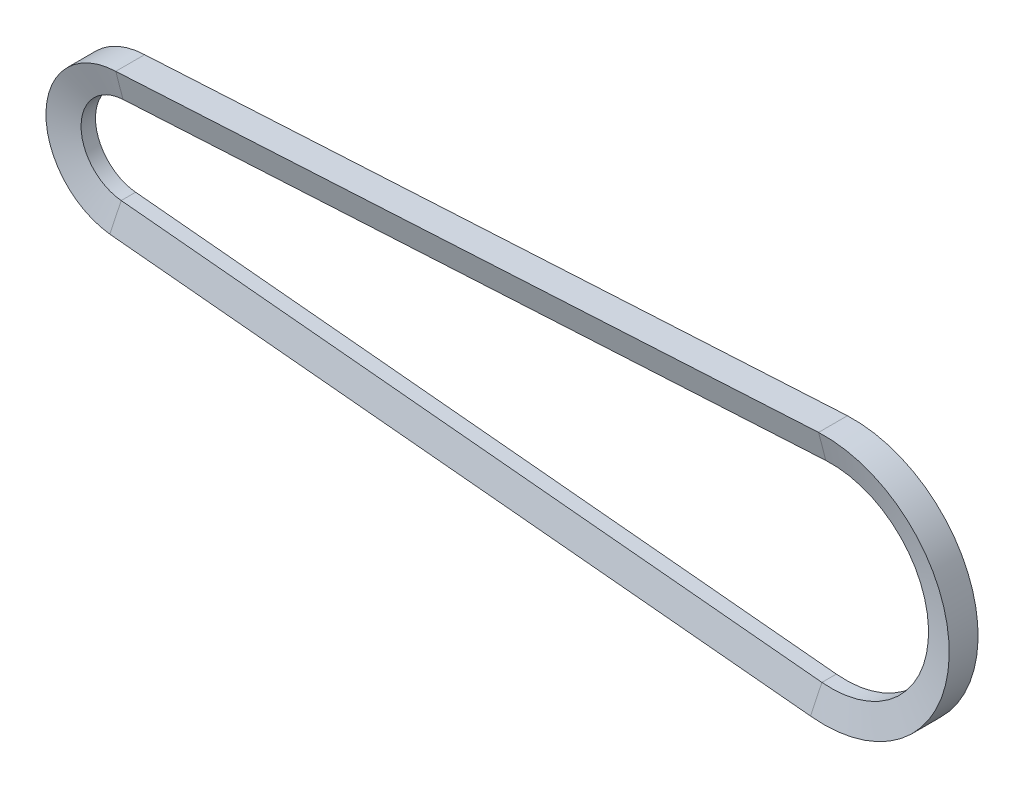
SolidWorks part; units mm, degrees
ref_plane "Front Plane" through (0, 0, 0) normal (0, 0, 1) x (1, 0, 0)
ref_plane "Top Plane" through (0, 0, 0) normal (0, 1, 0) x (1, 0, 0)
ref_plane "Right Plane" through (0, 0, 0) normal (1, 0, 0) x (0, 0, -1)
sketch "Sketch2" plane through (0, 0, 0) normal (0, 0, 1) x (1, 0, 0)
  line L0 (0, 0) -> (1, 0) construction
  line L1 (0, 0) -> (0, 1) construction
  line L2 (-1.2842, -13.4388) -> (-98.434, -4.155)
  line L3 (-98.1873, 8.1101) -> (-0.7428, 13.4796)
  arc A0 (-0.7428, 13.4796) -> (-1.2842, -13.4388) centre (0, 0) cw
  arc A1 (-98.434, -4.155) -> (-98.1873, 8.1101) centre (-97.8488, 1.9683) cw
ref_plane "Plane1" through (-0.7428, 0, 0) normal (1, 0, 0) x (0, 0, -1)
sketch "Sketch3" plane through (-0.7428, 0, 0) normal (1, 0, 0) x (0, 0, -1)
  line L0 (0, 23.3555) -> (0, 15.4053) construction
  line L1 (-2, 17.3525) -> (2, 17.3525)
  line L2 (2, 17.3525) -> (1, 13.4796)
  line L3 (1, 13.4796) -> (-1, 13.4796)
  line L4 (-2, 17.3525) -> (-1, 13.4796)
  point P3 (0, 0)
  point P8 (0, 13.4796)
  point P9 (0, 17.3525)
  dimension "D1" = 2
  dimension "D2" = 4
  dimension "D3" = 2
sweep "Sweep1" add profiles "Sketch3" path "Sketch2"
